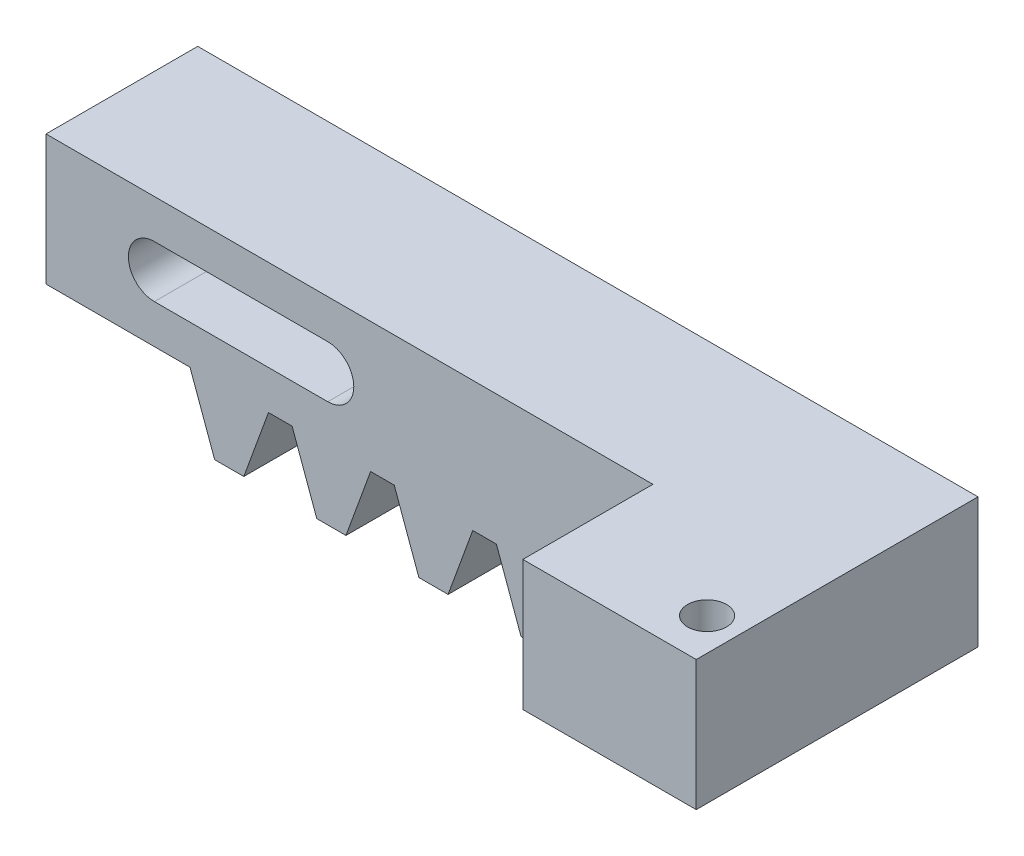
SolidWorks part; units mm, degrees
ref_plane "Front Plane" through (0, 0, 0) normal (0, 0, 1) x (1, 0, 0)
ref_plane "Top Plane" through (0, 0, 0) normal (0, 1, 0) x (1, 0, 0)
ref_plane "Right Plane" through (0, 0, 0) normal (1, 0, 0) x (0, 0, -1)
sketch "Sketch1" plane through (0, 0, 0) normal (0, 0, 1) x (1, 0, 0)
  line L0 (-16.7, 19.975) -> (19.3, 19.975)
  line L1 (19.3, 19.975) -> (19.3, 13.975)
  line L2 (19.3, 13.975) -> (17.1258, 13.975)
  line L3 (17.1258, 13.975) -> (15.9884, 10.85)
  line L4 (15.9884, 10.85) -> (14.6421, 10.85)
  line L5 (14.6421, 10.85) -> (13.5047, 13.975)
  line L6 (13.5047, 13.975) -> (12.4134, 13.975)
  line L7 (12.4134, 13.975) -> (11.276, 10.85)
  line L8 (11.276, 10.85) -> (9.9297, 10.85)
  line L9 (9.9297, 10.85) -> (8.7923, 13.975)
  line L10 (8.7923, 13.975) -> (7.701, 13.975)
  line L11 (7.701, 13.975) -> (6.5636, 10.85)
  line L12 (6.5636, 10.85) -> (5.2174, 10.85)
  line L13 (5.2174, 10.85) -> (4.0799, 13.975)
  line L14 (4.0799, 13.975) -> (2.9886, 13.975)
  line L15 (2.9886, 13.975) -> (1.8512, 10.85)
  line L16 (1.8512, 10.85) -> (0.505, 10.85)
  line L17 (0.505, 10.85) -> (-0.6324, 13.975)
  line L18 (-0.6324, 13.975) -> (-1.7238, 13.975)
  line L19 (-1.7238, 13.975) -> (-2.8612, 10.85)
  line L20 (-2.8612, 10.85) -> (-4.2074, 10.85)
  line L21 (-4.2074, 10.85) -> (-5.3448, 13.975)
  line L22 (-5.3448, 13.975) -> (-6.4361, 13.975)
  line L23 (-6.4361, 13.975) -> (-7.5735, 10.85)
  line L24 (-7.5735, 10.85) -> (-8.9198, 10.85)
  line L25 (-8.9198, 10.85) -> (-10.0572, 13.975)
  line L26 (-10.0572, 13.975) -> (-16.7, 13.975)
  line L27 (-16.7, 13.975) -> (-16.7, 19.975)
extrude "Boss-Extrude1" add sketch "Sketch1" along normal blind 7 from offset 13.5
sketch "Sketch2" plane through (0, 0, 0) normal (0, 0, 1) x (1, 0, 0)
  line L0 (11.3, 13.975) -> (19.3, 13.975)
  line L1 (19.3, 13.975) -> (19.3, 19.975)
  line L2 (19.3, 19.975) -> (11.3, 19.975)
  line L3 (11.3, 19.975) -> (11.3, 13.975)
extrude "Boss-Extrude2" add sketch "Sketch2" along normal blind 6 from offset 20.5
sketch "Sketch3" plane through (0, 0, 0) normal (0, 1, 0) x (1, 0, 0)
  circle A0 centre (17.8, -24.5) radius 0.9
extrude "Cut-Extrude1" cut sketch "Sketch3" against normal through all and the other way through all
sketch "Sketch4" plane through (0, 0, 0) normal (0, 0, 1) x (1, 0, 0)
  line L0 (-11.7, 15.775) -> (-3.7, 15.775)
  line L1 (-3.7, 15.775) -> (-3.7, 18.175)
  line L2 (-3.7, 18.175) -> (-11.7, 18.175)
  line L3 (-11.7, 18.175) -> (-11.7, 15.775)
extrude "Cut-Extrude2" cut sketch "Sketch4" against normal through all and the other way through all
sketch "Sketch5" plane through (0, 0, 0) normal (0, 0, 1) x (1, 0, 0)
  circle A0 centre (-11.7, 16.975) radius 1.2
  circle A1 centre (-3.7, 16.975) radius 1.2
extrude "Cut-Extrude3" cut sketch "Sketch5" against normal through all and the other way through all
